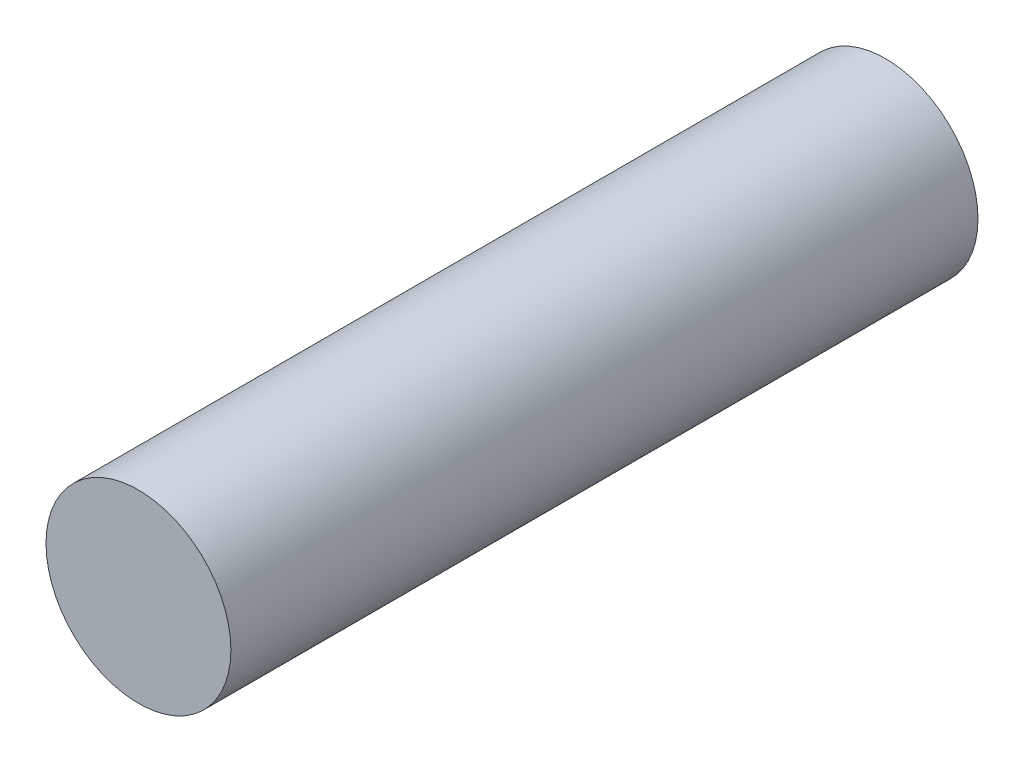
SolidWorks part; units mm, degrees
ref_plane "Front Plane" through (0, 0, 0) normal (0, 0, 1) x (1, 0, 0)
ref_plane "Top Plane" through (0, 0, 0) normal (0, 1, 0) x (1, 0, 0)
ref_plane "Right Plane" through (0, 0, 0) normal (1, 0, 0) x (0, 0, -1)
sketch "Sketch2" plane through (0, 0, 0) normal (0, 0, 1) x (1, 0, 0)
  circle A0 centre (1.9141, -1.569) radius 2.475
  dimension "D1" = 4.95
extrude "Boss-Extrude1" add sketch "Sketch2" along normal blind 20
